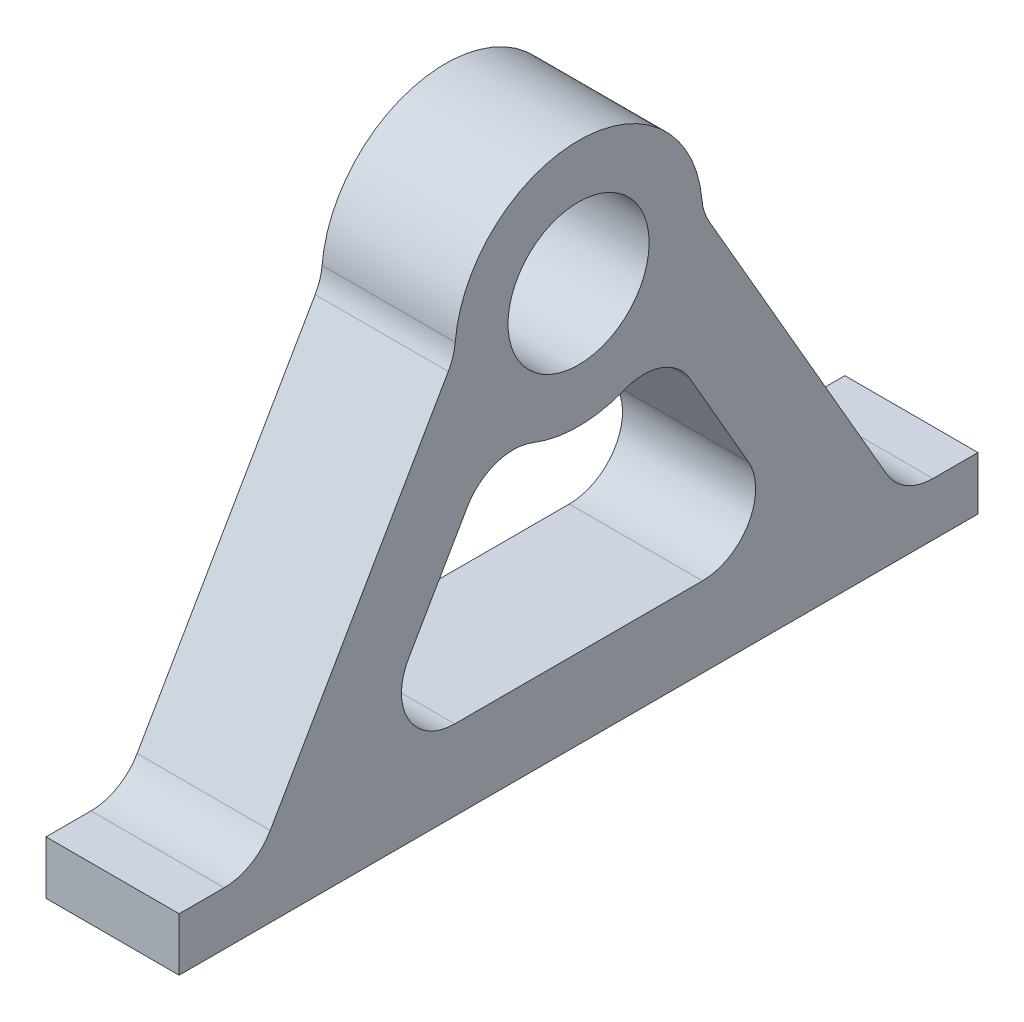
SolidWorks part; units mm, degrees
ref_plane "前视基准面" through (0, 0, 0) normal (0, 0, 1) x (1, 0, 0)
ref_plane "上视基准面" through (0, 0, 0) normal (0, 1, 0) x (1, 0, 0)
ref_plane "右视基准面" through (0, 0, 0) normal (1, 0, 0) x (0, 0, -1)
sketch "草图1" plane through (0, 0, 0) normal (1, 0, 0) x (0, 0, -1)
  line L0 (-4.65, 0) -> (-12.1556, -13)
  line L1 (-12.1556, -13) -> (-15, -13)
  line L2 (-15, -13) -> (-15, -15)
  line L3 (-15, -15) -> (15, -15)
  line L4 (0, -14.4833) -> (0, -10.3506) construction
  line L5 (15, -13) -> (15, -15)
  line L6 (12.1556, -13) -> (15, -13)
  line L7 (4.65, 0) -> (12.1556, -13)
  line L9 (-8.1141, -12) -> (-8.1141, -12)
  line L10 (-8.1141, -12) -> (-8.1141, -12)
  line L11 (-8.1141, -12) -> (8.1141, -12)
  line L12 (8.1141, -12) -> (8.1141, -12)
  line L13 (8.1141, -12) -> (8.1141, -12)
  line L15 (-3.157, -3.4141) -> (-8.1141, -12)
  line L16 (-1.5351, -0.6049) -> (-8.1141, -12) construction
  line L17 (3.157, -3.4141) -> (8.1141, -12)
  line L18 (1.5351, -0.6049) -> (8.1141, -12) construction
  circle A0 centre (0, 0) radius 2.65
  arc A1 (4.65, 0) -> (-4.65, 0) centre (0, 0) ccw
  circle A2 centre (0, 0) radius 4.65 construction
  arc A3 (-3.157, -3.4141) -> (3.157, -3.4141) centre (0, 0) ccw
  arc A4 (1.5351, -0.6049) -> (-1.5351, -0.6049) centre (0, 0) ccw construction
  point P13 (0, -15)
  point P27 (7.4495, -10.8488)
  point P28 (-8.1141, -12)
  point P29 (-3.0336, -3.4141)
  dimension "D1" = 5.3
  dimension "D7" = 2
  dimension "D3" = 30
  dimension "D4" = 30
  dimension "D5" = 2
  dimension "D8" = 15
  dimension "D2" = 2
  dimension "D6" = 3
extrude "凸台-拉伸1" add sketch "草图1" along normal mid plane 5
fillet "圆角1" radius 2 8 edges at (0, -13, -12.1556) (0, -13, 12.1556) (0, -12, -8.1141) (0, -12, 8.1141) (0, -3.4141, 3.157) (0, -3.4141, -3.157) (0, 0, -4.65) (0, 0, 4.65)
